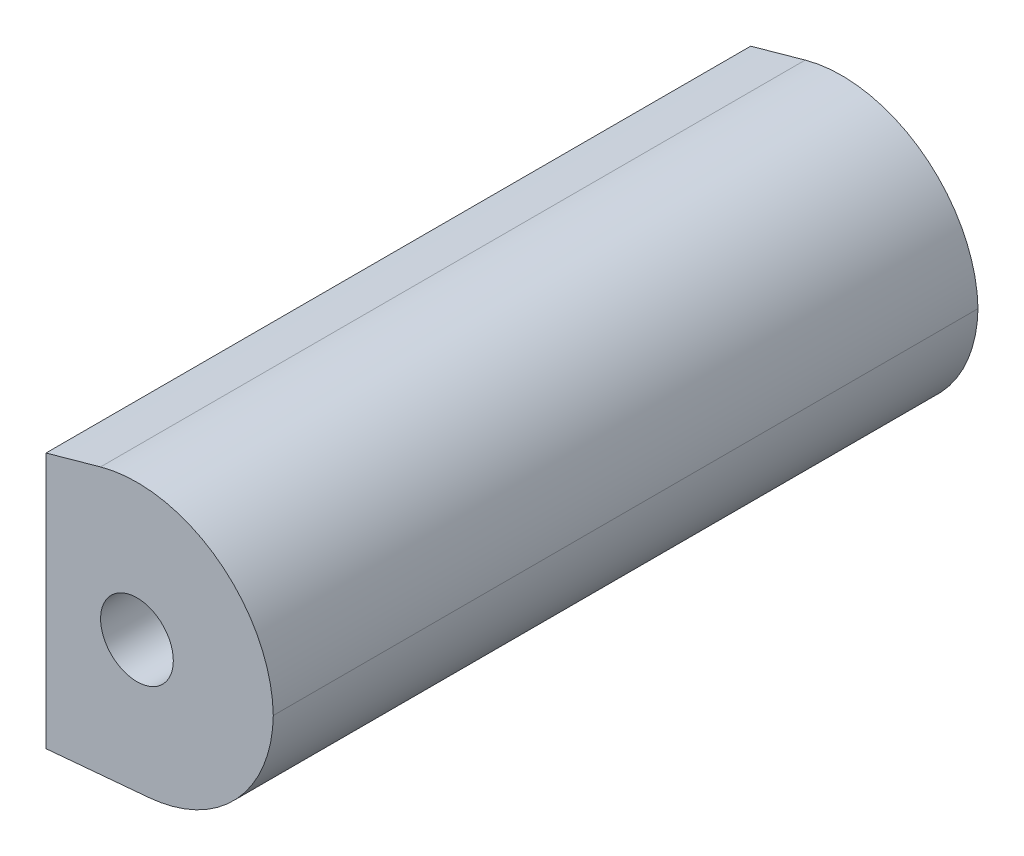
SolidWorks part; units mm, degrees
ref_plane "Front Plane" through (0, 0, 0) normal (0, 0, 1) x (1, 0, 0)
ref_plane "Top Plane" through (0, 0, 0) normal (0, 1, 0) x (1, 0, 0)
ref_plane "Right Plane" through (0, 0, 0) normal (1, 0, 0) x (0, 0, -1)
sketch "Sketch1" plane through (0, 0, 0) normal (0, 0, 1) x (1, 0, 0)
  circle A2 centre (19.9332, 5.0443) radius 2.032
  arc A3 (20.568, -2.2627) -> (27.5519, 5.1875) centre (19.9332, 5.3308) ccw
  arc A4 (27.5519, 5.1875) -> (17.8991, 12.3878) centre (19.9332, 5.0443) ccw
  spline S0 degree 3 poles (-43.5668, -9.1185) (-37.6773, -7.6477) (-27.7099, -7.0247) (-9.9845, -4.6043) (5.4332, -3.6912) (16.9241, -2.5678) (20.5343, -2.2656) (20.568, -2.2627) knots 0.794337 0.794337 0.794337 0.794337 0.852124 0.889612 0.965358 0.999676 1 1 1 1
  spline S1 degree 3 poles (17.8991, 12.3878) (11.779, 10.6925) (-2.9586, 6.4319) (-24.0803, -0.4076) (-34.9936, -4.7358) (-48.5374, -9.6348) (-43.5668, -9.1185) knots 0 0 0 0 0.056261 0.133579 0.179881 0.203823 0.203823 0.203823 0.203823
extrude "Boss-Extrude1" add sketch "Sketch1" along normal blind 39.37
sketch "Sketch3" plane through (0, 0, 39.37) normal (0, 0, 1) x (1, 0, 0)
  line L1 (-50.0795, 23.2318) -> (14.8519, 23.2318)
  line L2 (-50.0795, 23.2318) -> (-50.0795, -18.0197)
  line L3 (-50.0795, -18.0197) -> (14.8519, -18.0197)
  line L4 (14.8519, 23.2318) -> (14.8519, -18.0197)
  dimension "D1" = 12.7
extrude "Cut-Extrude2" cut sketch "Sketch3" against normal through all both
